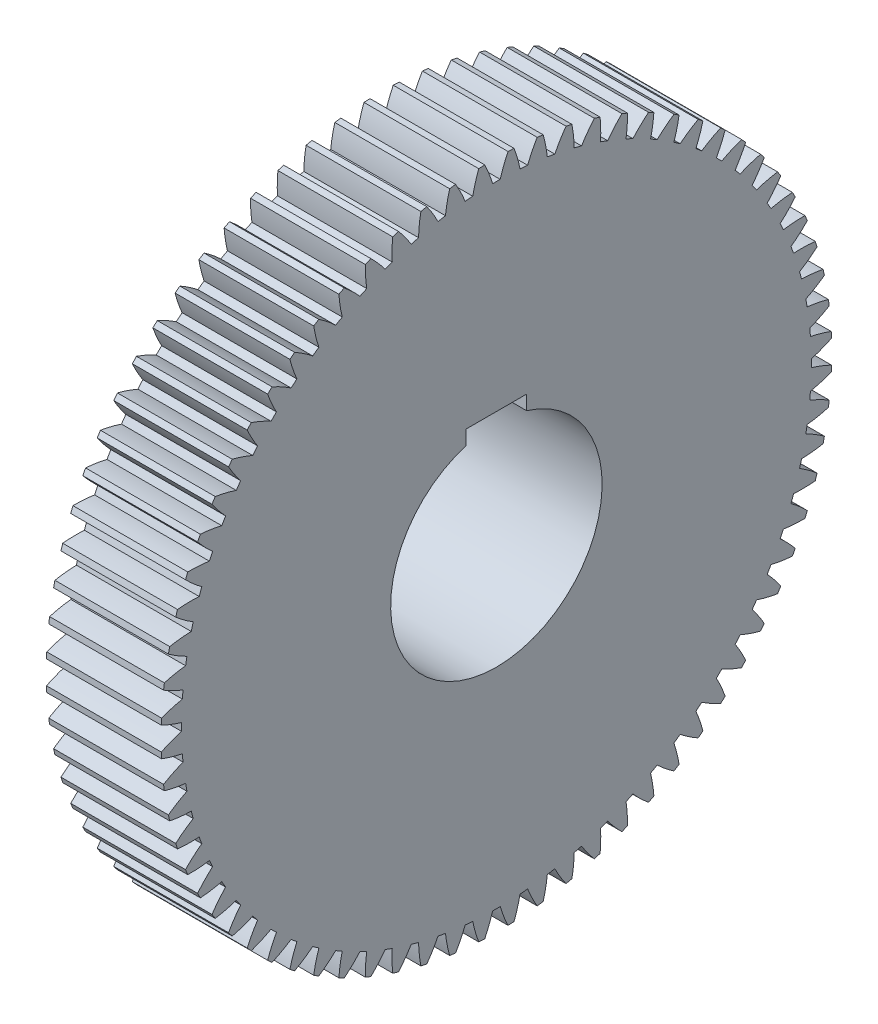
SolidWorks part; units mm, degrees
ref_plane "Plane1" through (0, 0, 0) normal (0, 0, 1) x (1, 0, 0)
ref_plane "Plane2" through (0, 0, 0) normal (0, 1, 0) x (1, 0, 0)
ref_plane "Plane3" through (0, 0, 0) normal (1, 0, 0) x (0, 0, -1)
sketch "HoldingSke" plane through (0, 0, 0) normal (0, 1, 0) x (1, 0, 0)
  line L0 (0, 0) -> (0.103, -0.317)
  line L1 (-15, 0) -> (100, 0) construction
  line L2 (0, 0) -> (-2.1039, 2.3779)
  line L3 (0, 0) -> (-11.863, 4.5341)
  line L4 (0, 0) -> (2.6687, 8.2133)
  line L5 (0, 0) -> (-58.0911, -21.6663)
  line L6 (0, 0) -> (-31.5006, -21.2535)
  line L7 (-2.1039, 2.3779) -> (11.2416, 62.9246)
  line L8 (-76.2, 54.61) -> (-71.3, 54.61)
  line L9 (-71.009, 38.7566) -> (-53.1078, 45.2721)
  line L10 (-76.2, 71.12) -> (104.1128, 71.12)
  line L11 (0, 0) -> (-38, 0)
  line L12 (-76.2, 101.6) -> (-76.093, 101.6)
  line L13 (24.9733, 27.94) -> (52.9518, 28.4284)
  line L14 (24.9733, 27.94) -> (24.9743, 27.94)
  line L15 (24.9733, 27.94) -> (100.4006, 29.5858)
  line L16 (-63.627, -3) -> (-12.827, -3)
  circle A0 centre (0, 0) radius 35
  circle A1 centre (0, 0) radius 42.5
  circle A2 centre (0, 0) radius 42.5
  circle A3 centre (0, 0) radius 35
  dimension "MHD" = 85
  dimension "Hub_dia" = 85
  dimension "Bore" = 70
  dimension "MBD" = 70
  dimension "Num_teeth" = 72
  dimension "Pitch" = 0.3333
  dimension "Overall_len" = 62
  dimension "Show_teeth" = 72
  dimension "Thickness" = 38
  dimension "OAL" = 62.0001
  dimension "T_dim" = 4.9
  dimension "Ap" = 20
  dimension "H" = 19.05
  dimension "Pitch_radius" = 180.3128
  dimension "Width" = 38
  dimension "Backlash" = 0.107
  dimension "Addendum_fac" = 1
  dimension "Dedendum_fac" = 1.25
  dimension "Clearance_fac" = 0.25
  dimension "Dedendum_add" = 0.001
  dimension "Module" = 3
sketch "BasProSke" plane through (0, 0, 0) normal (0, 1, 0) x (1, 0, 0)
  line L0 (-10, 0) -> (60, 0) construction
  line L1 (0, 0) -> (0, 111)
  line L2 (0, 0) -> (38, 0)
  line L3 (38, 0) -> (38, 111)
  line L4 (38, 111) -> (0, 111)
  dimension "Thickness" = 38
  dimension "Diameter" = 222
revolve "Base-Revolve" add sketch "BasProSke" angle 360 about L0
sketch "TooCutSke" plane through (0, 0, 0) normal (1, 0, 0) x (0, 0, -1)
  line L1 (0, 0) -> (0, 107) construction
  line L2 (0, 0) -> (-2.5433, 107.9701) construction
  line L3 (0, 0) -> (-9.4199, 215.7509) construction
  line L4 (-2.5433, 107.9701) -> (-4.7099, 107.8755) construction
  arc A0 (1.2601, 104.2414) -> (-1.2601, 104.2414) centre (0, 0) ccw
  arc A1 (3.8595, 110.9583) -> (-3.8595, 110.9583) centre (0, 0) ccw
  circle A2 centre (0, 0) radius 108 construction
  circle A3 centre (0, 0) radius 101.4868 construction
  arc A4 (-1.2601, 104.2414) -> (-3.8595, 110.9583) centre (-42.708, 92.063) ccw
  arc A5 (3.8595, 110.9583) -> (1.2601, 104.2414) centre (42.708, 92.063) ccw
  dimension "Root_dia" = 208.498
  dimension "Overcut_dia" = 222.0508
  dimension "Pitch_dia" = 216
  dimension "Base_dia" = 202.9736
  dimension "Flank_rad" = 43.2
  dimension "Half_ang" = 2.5
  dimension "Half_CT" = 2.1688
extrude "ToothCut" cut sketch "TooCutSke" along normal through all
fillet "Breaks" [suppressed] radius 0.06
fillet "RootFillets" [suppressed] radius 0.751
pattern_circular "TeethCuts" count 72 every 5 about axis through (-10, 0, 0) along (1, 0, 0) of "ToothCut", "RootFillets", "Breaks"
sketch "HubNeaOneSke" plane through (0, 0, 0) normal (-1, 0, 0) x (0, 0, 1)
  circle A0 centre (0, 0) radius 42.5
  dimension "Diameter" = 85
extrude "HubNearOne" add sketch "HubNeaOneSke" along normal blind 24.0001
sketch "HubNeaBotSke" plane through (0, 0, 0) normal (-1, 0, 0) x (0, 0, 1)
  circle A0 centre (0, 0) radius 42.5
  dimension "Diameter" = 85
extrude "HubNearBoth" [suppressed] add sketch "HubNeaBotSke" along normal blind 12
ref_plane "FarPln" through (38, 0, 0) normal (1, 0, 0) x (0, 0, -1)
sketch "HubFarSke" plane through (38, 0, 0) normal (1, 0, 0) x (0, 0, -1)
  circle A0 centre (0, 0) radius 42.5
  dimension "Diameter" = 85
extrude "HubFar" [suppressed] add sketch "HubFarSke" along normal blind 12
sketch "BorSke" plane through (0, 0, 0) normal (1, 0, 0) x (0, 0, -1)
  circle A0 centre (0, 0) radius 35
  dimension "Diameter" = 70
extrude "Bore" cut sketch "BorSke" along normal mid plane 124.0001
sketch "KeySke" plane through (0, 0, 0) normal (1, 0, 0) x (0, 0, -1)
  line L0 (-10, 0) -> (-10, 38.3)
  line L1 (-10, 38.3) -> (10, 38.3)
  line L2 (10, 38.3) -> (10, 0)
  line L3 (0, 0) -> (0, 34) construction
  line L4 (-10, 0) -> (10, 0)
  dimension "Offset" = 38.3
  dimension "Width" = 20
extrude "Keyway" cut sketch "KeySke" along normal mid plane 124.0001
pattern_circular "Keyway2" [suppressed] count 2 every 90 about axis through (-10, 0, 0) along (1, 0, 0)
equation "' \"Module@HoldingSke\" = 6.35"
equation "' \"Num_teeth@HoldingSke\" = 12"
equation "' \"Ap@HoldingSke\" =  20"
equation "' \"Ap@HoldingSke\" = 20"
equation "' \"Width@HoldingSke\" = 0.5 * 25.4"
equation "' \"Hub_dia@HoldingSke\"= 1 * 25.4"
equation "' \"Hub_dia@HoldingSke\" = 1 * 25.4"
equation "' \"Overall_len@HoldingSke\" = 1.0 * 25.4"
equation "' \"Bore@HoldingSke\" = 0.75 * 25.4"
equation "' \"T_dim@HoldingSke\" = 0.1 * 25.4"
equation "' \"Width@KeySke\" = 0.25 * 25.4"
equation "' \"Show_teeth@HoldingSke\" = 13"
equation "' \"Backlash@HoldingSke\" = 0.009 * 25.4"
equation "' \"Addendum_fac@HoldingSke\" = 1.0"
equation "' \"Dedendum_fac@HoldingSke\" = 1.25"
equation "' \"Dedendum_add@HoldingSke\" = 0.00005 * 25.4"
equation "' \"Clearance_fac@HoldingSke\" = 0.25"
equation "\"Pitch@HoldingSke\" = 1 / \"Module@HoldingSke\""
equation "\"Overcut_dia@TooCutSke\" = (\"Num_teeth@HoldingSke\" + 2 * \"Addendum_fac@HoldingSke\") / \"Pitch@HoldingSke\" + 0.002 * 25.4"
equation "\"Pitch_dia@TooCutSke\" = \"Num_teeth@HoldingSke\" / \"Pitch@HoldingSke\""
equation "\"Base_dia@TooCutSke\" = \"Num_teeth@HoldingSke\" / \"Pitch@HoldingSke\" * cos((\"Ap@HoldingSke\"  * 3.14159265 / 180))"
equation "\"Root_dia@TooCutSke\" = (\"Num_teeth@HoldingSke\" + 2) / \"Pitch@HoldingSke\" - 2 * (\"Addendum_fac@HoldingSke\" + \"Dedendum_fac@HoldingSke\") / \"Pitch@HoldingSke\" - \"Dedendum_add@HoldingSke\" * 2"
equation "\"Half_ang@TooCutSke\" = 180 / \"Num_teeth@HoldingSke\""
equation "\"Half_CT@TooCutSke\" = \"Num_teeth@HoldingSke\" / \"Pitch@HoldingSke\" * sin((3.14159265 / 2 / \"Num_teeth@HoldingSke\")) / 2 - 7 * \"Backlash@HoldingSke\" / 4"
equation "\"Flank_rad@TooCutSke\" = \"Num_teeth@HoldingSke\" / \"Pitch@HoldingSke\" / 5"
equation "\"Radius@RootFillets\" = \"Clearance_fac@HoldingSke\" / \"Pitch@HoldingSke\" + \"Dedendum_add@HoldingSke\""
equation "\"Break_rad@Breaks\" = 0.02 / \"Pitch@HoldingSke\""
equation "\"Thickness@HoldingSke\" = \"Width@HoldingSke\""
equation "\"OAL@HoldingSke\" = \"Thickness@HoldingSke\""
equation "\"MHD@HoldingSke\" = (\"Num_teeth@HoldingSke\" + 2) / \"Pitch@HoldingSke\" - 2 * (\"Addendum_fac@HoldingSke\" + \"Dedendum_fac@HoldingSke\")  / \"Pitch@HoldingSke\" - \"Dedendum_add@HoldingSke\" * 2"
equation "\"MBD@HoldingSke\" = (\"Num_teeth@HoldingSke\" + 2) / \"Pitch@HoldingSke\" - 2 * (\"Addendum_fac@HoldingSke\" + \"Dedendum_fac@HoldingSke\")  / \"Pitch@HoldingSke\" - \"Dedendum_add@HoldingSke\" * 2 - 0.002 * 25.4"
equation "\"MHD@HoldingSke\" = ((sgn( \"MHD@HoldingSke\" - \"Hub_dia@HoldingSke\" )-1)*( \"MHD@HoldingSke\" - \"Hub_dia@HoldingSke\" ))/-2+ \"Hub_dia@HoldingSke\""
equation "\"MBD@HoldingSke\" = ((sgn( \"MBD@HoldingSke\" - \"Bore@HoldingSke\" )-1)*( \"MBD@HoldingSke\" - \"Bore@HoldingSke\" ))/-2+ \"Bore@HoldingSke\""
equation "\"OAL@HoldingSke\" = ((sgn( \"OAL@HoldingSke\" - \"Overall_len@HoldingSke\" )+1)*( \"OAL@HoldingSke\" - \"Overall_len@HoldingSke\" ))/2 + \"Overall_len@HoldingSke\" + 0.000002 * 25.4"
equation "\"Num_teeth@TeethCuts\" = int( \"Show_teeth@HoldingSke\" ) + 1"
equation "\"Num_teeth@TeethCuts\" = ((sgn( \"Num_teeth@TeethCuts\" - \"Num_teeth@HoldingSke\" )-1)*( \"Num_teeth@TeethCuts\" - \"Num_teeth@HoldingSke\" ))/-2+ \"Num_teeth@HoldingSke\""
equation "\"Num_teeth@TeethCuts\" = ((sgn( \"Num_teeth@TeethCuts\" - 2.0)+1)*( \"Num_teeth@TeethCuts\" - 2.0))/2 +2.0"
equation "\"Angle@TeethCuts\" = 360.0 / \"Num_teeth@HoldingSke\""
equation "\"Diameter@BasProSke\" = (\"Num_teeth@HoldingSke\" + 2 * \"Addendum_fac@HoldingSke\") / \"Pitch@HoldingSke\""
equation "\"Thickness@BasProSke\"  = \"Thickness@HoldingSke\""
equation "' \"Fillet_rad@BasProSke\" =  \"Thickness@HoldingSke\" * 0.05"
equation "' \"Fillet_rad@BasProSke\" = \"Thickness@HoldingSke\" * 0.05"
equation "\"MHD@HoldingSke\" = ((sgn( \"MHD@HoldingSke\" - \"Root_dia@TooCutSke\" )-1)*( \"MHD@HoldingSke\" - \"Root_dia@TooCutSke\" ))/-2+ \"Root_dia@TooCutSke\""
equation "\"Diameter@HubNeaOneSke\" = \"MHD@HoldingSke\""
equation "\"Length@HubNearOne\" = \"OAL@HoldingSke\" - \"Thickness@BasProSke\""
equation "\"Diameter@HubNeaBotSke\" = \"MHD@HoldingSke\""
equation "\"Length@HubNearBoth\" = ( \"OAL@HoldingSke\" - \"Thickness@BasProSke\" ) / 2.0"
equation "\"Thickness@FarPln\" = \"Thickness@BasProSke\""
equation "\"Diameter@HubFarSke\" = \"MHD@HoldingSke\""
equation "\"Length@HubFar\" = ( \"OAL@HoldingSke\" - \"Thickness@BasProSke\" ) / 2.0"
equation "\"Diameter@BorSke\" = \"MBD@HoldingSke\""
equation "\"D1@Bore\" = \"OAL@HoldingSke\" * 2.0"
equation "\"D1@Keyway\" = \"OAL@HoldingSke\" * 2.0"
